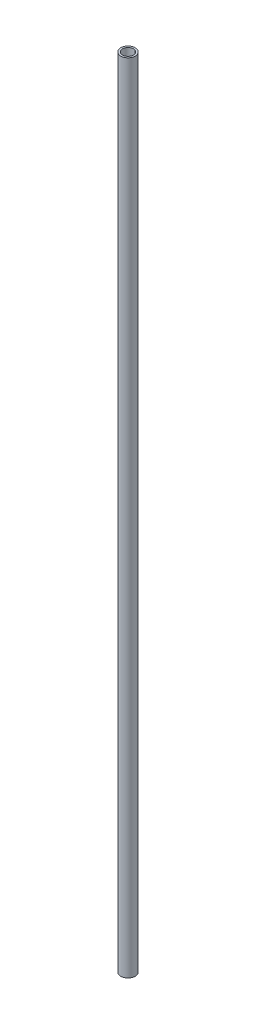
SolidWorks part; units mm, degrees
material "ABS"
ref_plane "Front Plane" through (0, 0, 0) normal (0, 0, 1) x (1, 0, 0)
ref_plane "Top Plane" through (0, 0, 0) normal (0, 1, 0) x (1, 0, 0)
ref_plane "Right Plane" through (0, 0, 0) normal (1, 0, 0) x (0, 0, -1)
sketch "Sketch1" plane through (0, 0, 0) normal (0, 1, 0) x (1, 0, 0)
  circle A0 centre (0, 0) radius 3.75
  circle A1 centre (0, 0) radius 5
  dimension "D1" = 7.5
  dimension "D2" = 10
extrude "Boss-Extrude1" add sketch "Sketch1" along normal mid plane 550
